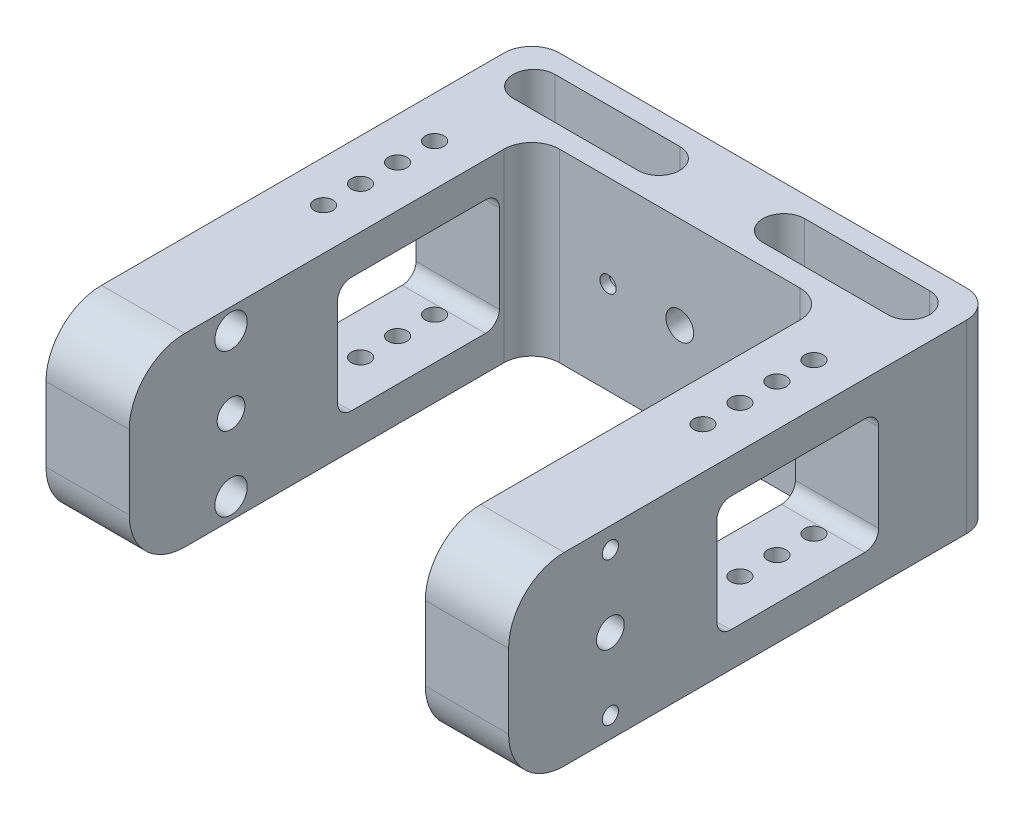
SolidWorks part; units mm, degrees
ref_plane "前视基准面" through (0, 0, 0) normal (0, 0, 1) x (1, 0, 0)
ref_plane "上视基准面" through (0, 0, 0) normal (0, 1, 0) x (1, 0, 0)
ref_plane "右视基准面" through (0, 0, 0) normal (1, 0, 0) x (0, 0, -1)
other "Configuration Table"
sketch "草图1" plane through (0, 0, 0) normal (0, 1, 0) x (1, 0, 0)
  line L0 (-18, 0) -> (0, 0)
  line L9 (-100, 90) -> (0, 90)
  line L10 (-100, 90) -> (-100, 0)
  line L11 (-100, 0) -> (-82, 0)
  line L12 (0, 90) -> (0, 0)
  line L13 (-100, 90) -> (0, 0) construction
  line L14 (-100, 0) -> (0, 90) construction
  line L16 (-82, 0) -> (-82, 72)
  line L17 (-82, 72) -> (-18, 72)
  line L18 (-18, 0) -> (-18, 72)
  point P0 (0, 0)
  point P1 (-50, 45)
  dimension "D1" = 100
  dimension "D2" = 90
  dimension "D3" = 64
  dimension "D4" = 18
  dimension "D5" = 18
extrude "凸台-拉伸1" add sketch "草图1" along normal mid plane 40
sketch "草图2" plane through (-100, 0, 0) normal (-1, 0, 0) x (0, 0, 1)
  circle A0 centre (-7, 0) radius 3
  circle A1 centre (-7, 15.5) radius 1.75
  circle A2 centre (-7, -15.5) radius 1.75
  point P7 (0, 0)
  point P8 (-7, -15.5)
  point P9 (0, 0)
  point P10 (0, 0)
  dimension "D1" = 6
  dimension "D5" = 3.5
  dimension "D6" = 3.5
  dimension "D2" = 7
  dimension "D3" = 15.5
  dimension "D4" = 15.5
extrude "切除-拉伸1" cut sketch "草图2" against normal blind 112
sketch "草图4" plane through (-18, 0, 0) normal (-1, 0, 0) x (0, 0, 1)
  line L0 (0, 20) -> (0, -20) construction
  line L1 (-62, 12.5) -> (-33, 12.5)
  line L2 (-65, 9.5) -> (-65, -9.5)
  line L3 (-62, -12.5) -> (-33, -12.5)
  line L4 (-30, 9.5) -> (-30, -9.5)
  arc A1 (-65, -9.5) -> (-62, -12.5) centre (-62, -9.5) ccw
  arc A2 (-33, -12.5) -> (-30, -9.5) centre (-33, -9.5) ccw
  arc A3 (-33, 12.5) -> (-30, 9.5) centre (-33, 9.5) cw
  arc A4 (-62, 12.5) -> (-65, 9.5) centre (-62, 9.5) ccw
  point P4 (-30, 0)
  point P12 (-30, -12.5)
  point P15 (-30, 12.5)
  point P18 (-65, 12.5)
  dimension "D4" = 3
  dimension "D1" = 35
  dimension "D2" = 30
  dimension "D3" = 25
extrude "切除-拉伸2" cut sketch "草图4" against normal blind 61 and the other way blind 123
sketch "草图5" plane through (0, 0, 0) normal (0, 0, 1) x (1, 0, 0)
  line L0 (-18, -20) -> (0, -20) construction
  line L1 (0, -20) -> (0, 20) construction
  line L2 (0, 20) -> (-18, 20) construction
  line L3 (-18, 20) -> (-18, -20) construction
  line L4 (-100, -20) -> (-82, -20) construction
  line L5 (-82, -20) -> (-82, 20) construction
  line L6 (-82, 20) -> (-100, 20) construction
  line L7 (-100, 20) -> (-100, -20) construction
  line L8 (-18, -20) -> (0, -20)
  line L9 (0, -20) -> (0, 20)
  line L10 (0, 20) -> (-18, 20)
  line L11 (-18, 20) -> (-18, -20)
  line L12 (-100, -20) -> (-82, -20)
  line L13 (-82, -20) -> (-82, 20)
  line L14 (-82, 20) -> (-100, 20)
  line L15 (-100, 20) -> (-100, -20)
extrude "凸台-拉伸3" add sketch "草图5" along normal blind 15
sketch "草图6" plane through (0, 20, 0) normal (0, 1, 0) x (1, 0, 0)
  line L0 (-50, 90) -> (-50, -20.2588) construction
  line L1 (0, 90) -> (-100, 90) construction
  line L2 (-82, -15) -> (-82, 72) construction
  line L3 (-82, 72) -> (-18, 72) construction
  circle A0 centre (-91, 60) radius 2
  circle A1 centre (-91, 52) radius 2
  circle A2 centre (-91, 44) radius 2
  circle A3 centre (-91, 36) radius 2
  circle A4 centre (-9, 36) radius 2
  circle A5 centre (-9, 44) radius 2
  circle A6 centre (-9, 52) radius 2
  circle A7 centre (-9, 60) radius 2
  point P10 (-91, 37.2543)
  dimension "D3" = 4
  dimension "D1" = 9
  dimension "D2" = 12
  dimension "D5" = 8
  dimension "D4" = 4
extrude "切除-拉伸3" cut sketch "草图6" against normal through all both and the other way through all
sketch "草图7" plane through (0, 20, 0) normal (0, 1, 0) x (1, 0, 0)
  line L0 (-50, 90) -> (-50, 18.8642) construction
  line L1 (0, 90) -> (-100, 90) construction
  line L2 (-90.5, 81) -> (-63.5, 81) construction
  line L3 (-90.5, 85.5) -> (-63.5, 85.5)
  line L4 (-90.5, 76.5) -> (-63.5, 76.5)
  line L5 (-82, 72) -> (-18, 72) construction
  line L6 (-9.5, 81) -> (-36.5, 81) construction
  line L7 (-9.5, 85.5) -> (-36.5, 85.5)
  line L8 (-9.5, 76.5) -> (-36.5, 76.5)
  arc A0 (-90.5, 85.5) -> (-90.5, 76.5) centre (-90.5, 81) ccw
  arc A1 (-63.5, 76.5) -> (-63.5, 85.5) centre (-63.5, 81) ccw
  arc A2 (-9.5, 85.5) -> (-9.5, 76.5) centre (-9.5, 81) cw
  arc A3 (-36.5, 76.5) -> (-36.5, 85.5) centre (-36.5, 81) cw
  point P2 (-77, 81)
  point P15 (-23, 81)
  dimension "D1" = 9
  dimension "D2" = 9
  dimension "D3" = 27
  dimension "D4" = 27
extrude "切除-拉伸4" cut sketch "草图7" against normal through all both and the other way through all
fillet "圆角1" radius 6 4 edges at (-82, 0, -72) (-18, 0, -72) (0, 0, -90) (-100, 0, -90)
fillet "圆角2" radius 12 4 edges at (-9, -20, 15) (-9, 20, 15) (-91, -20, 15) (-91, 20, 15)
sketch "草图9" plane through (0, 0, -90) normal (0, 0, -1) x (-1, 0, 0)
  circle A0 centre (50, 0) radius 7.5
  point P2 (0, 0)
  dimension "D2" = 15
  dimension "D1" = 50
extrude "切除-拉伸6" cut sketch "草图9" against normal blind 8
sketch "草图10" plane through (0, 0, -72) normal (0, 0, 1) x (1, 0, 0)
  circle A0 centre (-50, 0) radius 3
  point P2 (0, 0)
  dimension "D2" = 6
  dimension "D1" = 50
extrude "切除-拉伸7" cut sketch "草图10" against normal blind 16
sketch "草图11" plane through (0, 0, -72) normal (0, 0, 1) x (1, 0, 0)
  circle A0 centre (-34.5, 0) radius 1.75
  circle A1 centre (-65.5, 0) radius 1.75
  circle A2 centre (-50, 0) radius 3 construction
  circle A3 centre (-50, 0) radius 3
  point P7 (0, 0)
  point P8 (-35.8028, -6.2201)
  point P9 (0, 0)
  dimension "D4" = 3.5
  dimension "D5" = 3.5
  dimension "D1" = 31
  dimension "D2" = 15.5
  dimension "D3" = 15.5
extrude "切除-拉伸8" cut sketch "草图11" against normal blind 23 contours A3 | A1 | A0
sketch "草图12" plane through (0, 0, -90) normal (0, 0, -1) x (-1, 0, 0)
  circle A0 centre (34.5, 0) radius 3.5
  circle A1 centre (65.5, 0) radius 3.5
  dimension "D1" = 7
  dimension "D2" = 7
extrude "切除-拉伸9" cut sketch "草图12" against normal blind 16
ref_plane "基准面1" through (-50, 0, 0) normal (1, 0, 0) x (0, 0, -1)
sketch "草图14" plane through (-50, 0, 0) normal (1, 0, 0) x (0, 0, -1)
  circle A0 centre (7, 15.5) radius 3.5
  circle A1 centre (7, -15.5) radius 3.5
  dimension "D1" = 7
  dimension "D2" = 7
extrude "切除-拉伸10" cut sketch "草图14" against normal mid plane 90
